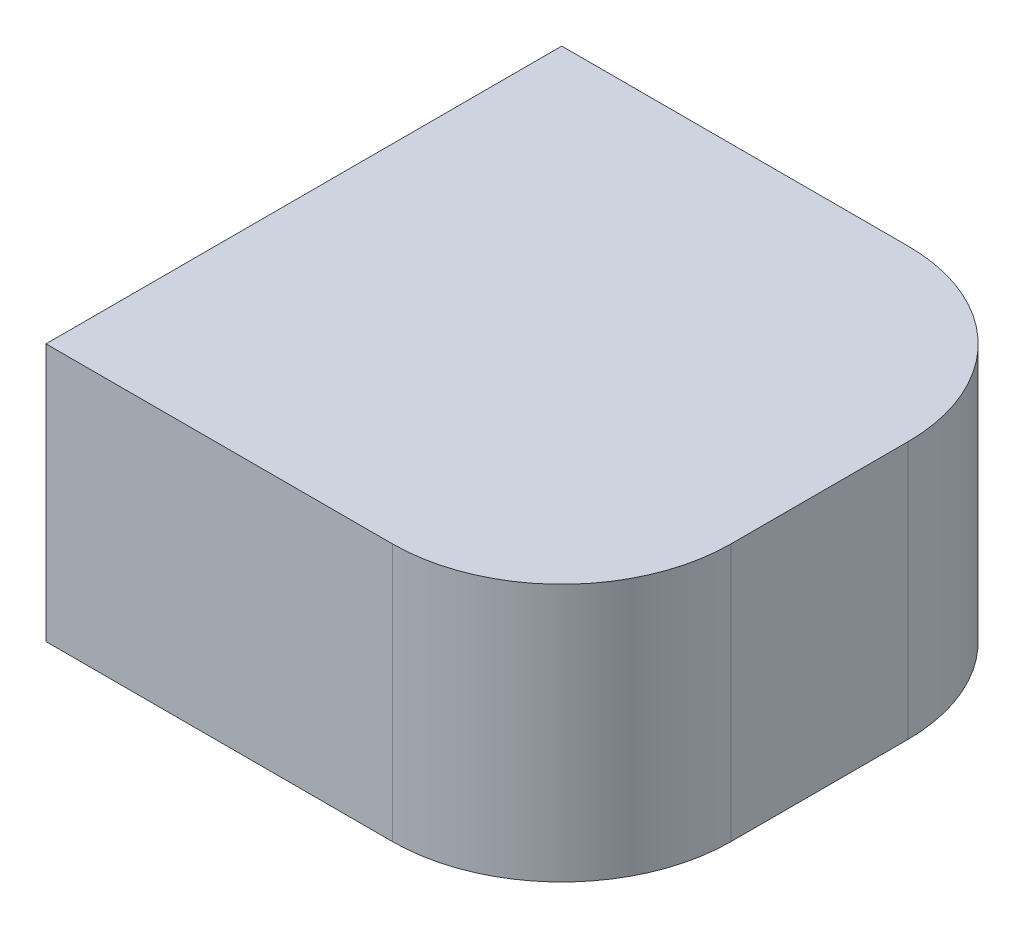
SolidWorks part; units mm, degrees
ref_plane "Alzado" through (0, 0, 0) normal (0, 0, 1) x (1, 0, 0)
ref_plane "Planta" through (0, 0, 0) normal (0, 1, 0) x (1, 0, 0)
ref_plane "Vista lateral" through (0, 0, 0) normal (1, 0, 0) x (0, 0, -1)
sketch "Croquis1" plane through (0, 0, 0) normal (0, 1, 0) x (1, 0, 0)
  line L1 (-23, 0) -> (-70, 0)
  line L2 (0, -23) -> (0, -47)
  line L3 (-23, -70) -> (-70, -70)
  line L4 (-70, 0) -> (-70, -70)
  arc A0 (-23, 0) -> (0, -23) centre (-23, -23) cw
  arc A1 (0, -47) -> (-23, -70) centre (-23, -47) cw
  point P7 (0, 0)
  point P10 (0, -70)
  dimension "D3" = 23
  dimension "D1" = 70
  dimension "D2" = 70
extrude "Saliente-Extruir1" add sketch "Croquis1" along normal blind 35
sketch "Croquis2" plane through (0, 0, 0) normal (0, 0, -1) x (-1, 0, 0)
  line L0 (70, 35) -> (70, 0) construction
  line L1 (65, 29.5) -> (68, 29.5)
  line L2 (65, 29.5) -> (65, 5.5)
  line L3 (65, 5.5) -> (68, 5.5)
  line L4 (68, 29.5) -> (68, 5.5)
  point P6 (70, 17.5)
  point P7 (68, 17.5)
  dimension "D1" = 2
  dimension "D2" = 24
  dimension "D3" = 3
extrude "Cortar-Extruir1" cut sketch "Croquis2" against normal blind 22
